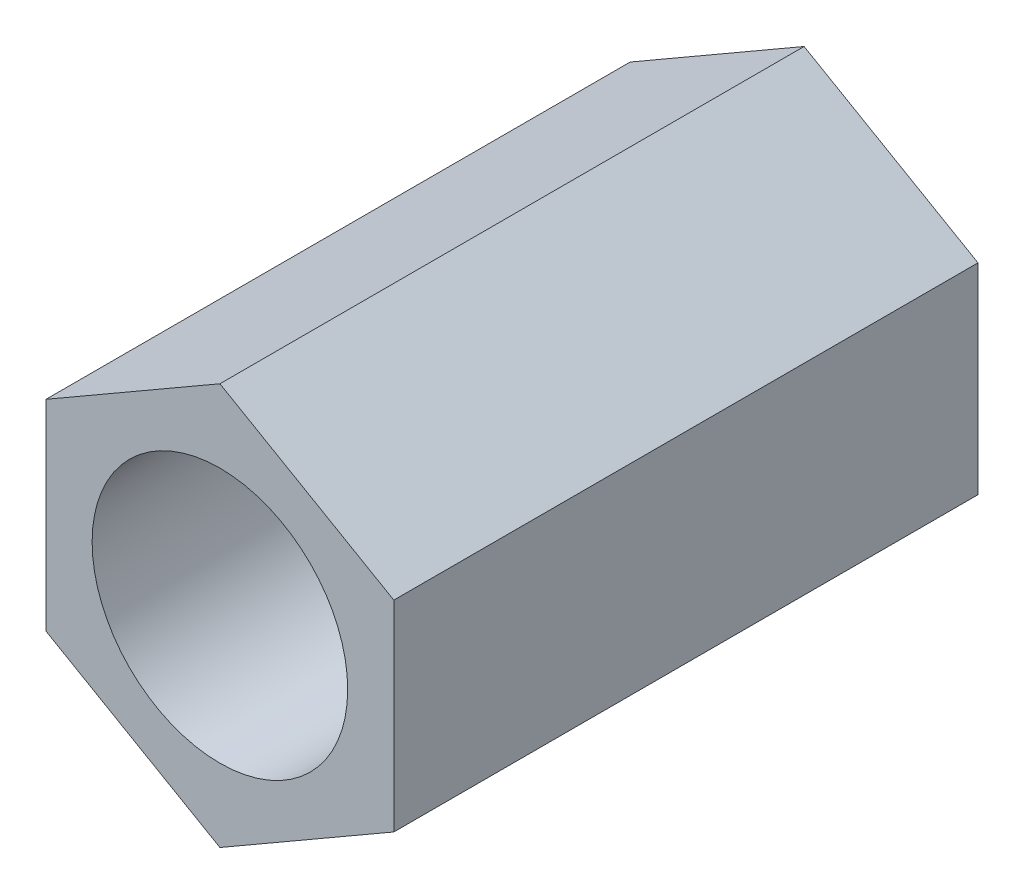
SolidWorks part; units mm, degrees
ref_plane "Front Plane" through (0, 0, 0) normal (0, 0, 1) x (1, 0, 0)
ref_plane "Top Plane" through (0, 0, 0) normal (0, 1, 0) x (1, 0, 0)
ref_plane "Right Plane" through (0, 0, 0) normal (1, 0, 0) x (0, 0, -1)
sketch "Sketch1" plane through (0, 0, 0) normal (0, 0, 1) x (1, 0, 0)
  line L1 (0, 2.75) -> (-2.3816, 1.375)
  line L2 (-2.3816, 1.375) -> (-2.3816, -1.375)
  line L3 (-2.3816, -1.375) -> (0, -2.75)
  line L4 (0, -2.75) -> (2.3816, -1.375)
  line L5 (2.3816, -1.375) -> (2.3816, 1.375)
  line L6 (2.3816, 1.375) -> (0, 2.75)
  circle A0 centre (0, 0) radius 2.75 construction
  circle A1 centre (0, 0) radius 2.3816 construction
  dimension "D1" = 5.5
extrude "Boss-Extrude1" add sketch "Sketch1" along normal blind 8
sketch "Sketch2" plane through (0, 0, 8) normal (0, 0, 1) x (1, 0, 0)
  circle A0 centre (0, 0) radius 1.75
extrude "Cut-Extrude1" cut sketch "Sketch2" against normal through all
